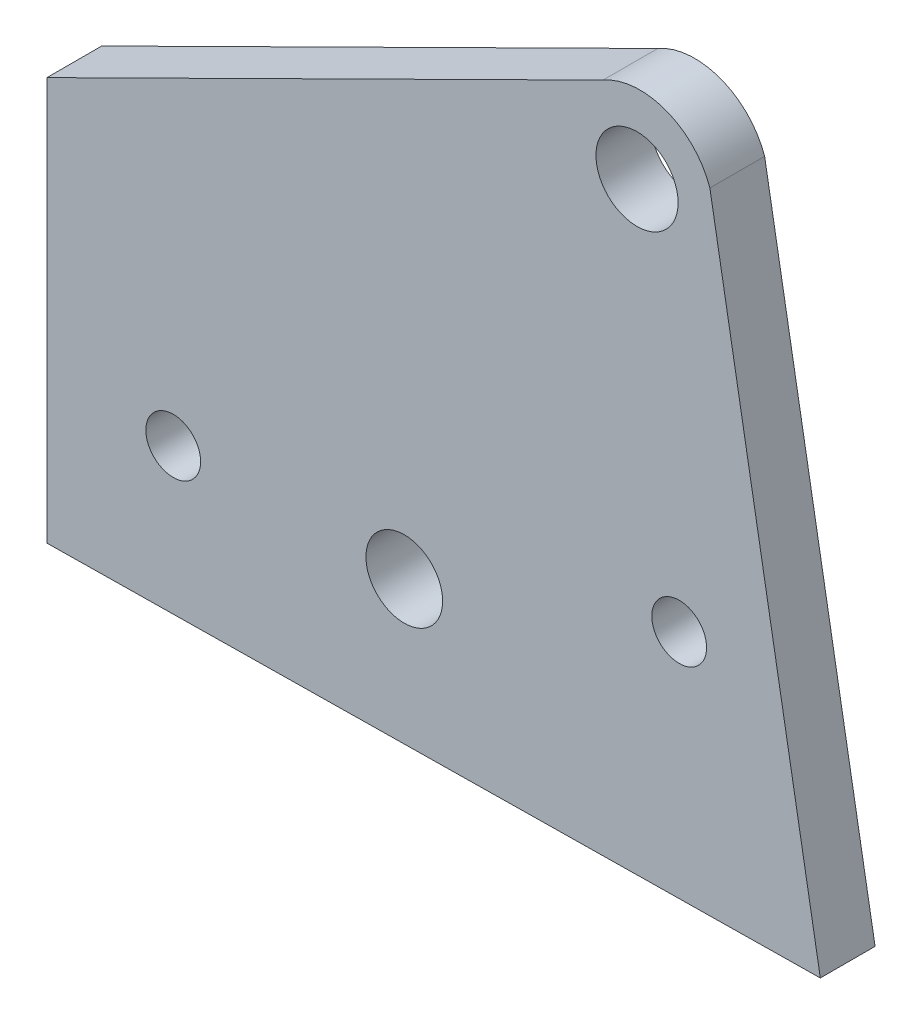
SolidWorks part; units mm, degrees
ref_plane "Front Plane" through (0, 0, 0) normal (0, 0, 1) x (1, 0, 0)
ref_plane "Top Plane" through (0, 0, 0) normal (0, 1, 0) x (1, 0, 0)
ref_plane "Right Plane" through (0, 0, 0) normal (1, 0, 0) x (0, 0, -1)
sketch "Sketch1" plane through (0, 0, 0) normal (0, 0, 1) x (1, 0, 0)
  line L0 (-27.2485, 19.6861) -> (-57.7075, 4.5736)
  line L1 (-57.7075, 4.5736) -> (-57.7075, -17.5104)
  line L2 (-57.7075, -17.5104) -> (-15.3403, -16.9572)
  line L3 (-15.3403, -16.9572) -> (-21.3908, 17.4964)
  circle A0 centre (-38.1318, -9.4216) radius 2.1
  arc A1 (-21.3908, 17.4964) -> (-27.2485, 19.6861) centre (-25.2182, 16.1875) ccw
  circle A2 centre (-25.3818, 15.9237) radius 2.25
  circle A3 centre (-23.0715, -4.4001) radius 1.5
  circle A4 centre (-50.7877, -9.4355) radius 1.5
  dimension "D1" = 4.2
extrude "Boss-Extrude2" add sketch "Sketch1" along normal blind 3
